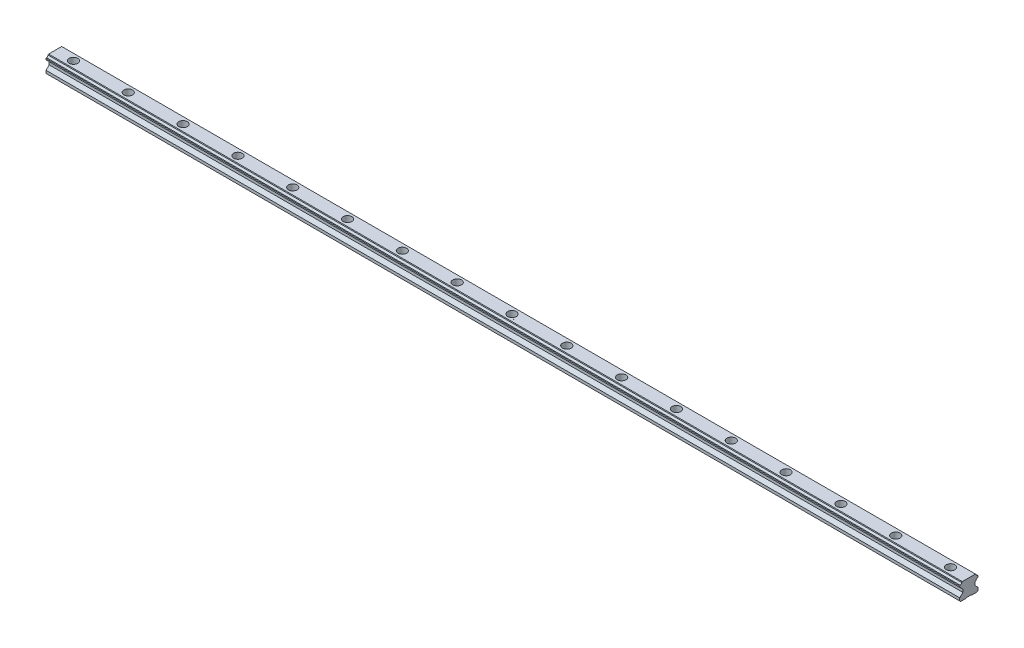
SolidWorks part; units mm, degrees
material "Alloy Steel"
ref_plane "Front Plane" through (0, 0, 0) normal (0, 0, 1) x (1, 0, 0)
ref_plane "Top Plane" through (0, 0, 0) normal (0, 1, 0) x (1, 0, 0)
ref_plane "Right Plane" through (0, 0, 0) normal (1, 0, 0) x (0, 0, -1)
sketch "Sketch6" plane through (0, 48.7499, 0) normal (0, 1, 0) x (-1, 0, 0)
  line L0 (-67, -46.0009) -> (-233, -46.0009) construction
  line L1 (-124.6001, -68.0009) -> (-124.6001, -24.0009)
  line L2 (-175.4001, -68.0009) -> (-175.4001, -24.0009)
  line L3 (-70, -56.0009) -> (-70, -36.0009)
  line L4 (-116.0002, -67.0009) -> (-116.0002, -25.0009)
  line L5 (-115.0002, -67.0009) -> (-115.0002, -25.0009)
  line L6 (-113.0002, -56.4008) -> (-113.0002, -35.601)
  line L7 (-115.0002, -67.0009) -> (-124.6001, -67.0009)
  line L8 (-113.0002, -56.4008) -> (-115.0002, -58.4008)
  line L9 (-70, -56.0009) -> (-113.0002, -56.0009)
  line L10 (-70, -53.1609) -> (-113.0002, -53.1609)
  line L11 (-113.0002, -35.601) -> (-115.0002, -33.601)
  line L12 (-115.0002, -25.0009) -> (-124.6001, -25.0009)
  line L13 (-70, -38.841) -> (-103.6509, -38.841)
  line L14 (-70, -36.0009) -> (-104.6381, -36.0009)
  line L15 (-230, -56.0009) -> (-230, -36.0009)
  line L16 (-230, -36.0009) -> (-187, -36.0009)
  line L17 (-184, -67.0009) -> (-184, -25.0009)
  line L18 (-185, -67.0009) -> (-185, -25.0009)
  line L19 (-187, -56.4008) -> (-187, -35.601)
  line L20 (-185, -67.0009) -> (-175.4001, -67.0009)
  line L21 (-187, -56.4008) -> (-185, -58.4008)
  line L22 (-230, -56.0009) -> (-187, -56.0009)
  line L23 (-230.0002, -53.1609) -> (-187, -53.1609)
  line L24 (-187, -35.601) -> (-185, -33.601)
  line L25 (-185, -25.0009) -> (-175.4001, -25.0009)
  line L26 (-230.0002, -38.841) -> (-187, -38.841)
  line L27 (-210, -52.0009) -> (-210, -40.0009) construction
  line L28 (-90, -52.0009) -> (-90, -40.0009) construction
  line L29 (-150, -52.0009) -> (-150, -40.0009) construction
  line L30 (-182.2712, -57.0009) -> (-187.2456, -57.0009) construction
  line L31 (-182.2712, -35.0009) -> (-187.2456, -35.0009) construction
  line L32 (-117.7288, -57.0009) -> (-112.7544, -57.0009) construction
  line L33 (-117.7288, -35.0009) -> (-112.7544, -35.0009) construction
  line L34 (-113.0003, -42.0009) -> (-113.0003, -50.0009)
  line L35 (-109.7003, -50.0009) -> (-113.0003, -50.0009)
  line L36 (-111.3204, -42.0009) -> (-113.0003, -42.0009)
  line L37 (-105.7003, -46.0009) -> (-105.7003, -44.3288)
  line L38 (-113.0003, -50.0009) -> (-115.0002, -50.0009)
  line L39 (-113.0003, -42.0009) -> (-115.0002, -42.0009)
  line L40 (-103.483, -36.4794) -> (-107.9177, -34.6425)
  line L41 (-103.6848, -39.3183) -> (-109.7824, -36.7926)
  line L42 (-103.483, -36.4794) -> (-103.6848, -39.3183)
  line L43 (-107.9177, -34.6425) -> (-109.7824, -36.7926)
  line L44 (-104.4235, -43.0391) -> (-104.8382, -44.0402)
  line L45 (-111.8911, -39.946) -> (-112.3058, -40.947)
  line L46 (-105.6176, -44.363) -> (-104.8382, -44.0402)
  line L47 (-106.0608, -41.7115) -> (-106.9334, -43.8181)
  line L48 (-109.7946, -40.1649) -> (-110.6671, -42.2715)
  line L49 (-105.6176, -44.363) -> (-111.9829, -41.7265)
  line L50 (-112.3058, -40.947) -> (-111.9829, -41.7265)
  line L51 (-104.6533, -42.2945) -> (-111.2021, -39.5819)
  line L52 (-110.2333, -38.841) -> (-113.0002, -38.841)
  line L53 (-109.0958, -36.0009) -> (-113.0002, -36.0009)
  line L54 (-124.6001, -53.0009) -> (-175.4001, -53.0009)
  line L55 (-124.6001, -68.0009) -> (-175.4001, -68.0009)
  line L56 (-124.6001, -39.0009) -> (-175.4001, -39.0009)
  line L57 (-124.6001, -24.0009) -> (-175.4001, -24.0009)
  line L58 (-135.5002, -30.0009) -> (-128.5002, -30.0009) construction
  line L59 (-132.0002, -33.5009) -> (-132.0002, -26.5009) construction
  line L60 (-135.5002, -62.0009) -> (-128.5002, -62.0009) construction
  line L61 (-132.0002, -58.5009) -> (-132.0002, -65.5009) construction
  line L62 (-164.4998, -62.0009) -> (-171.4998, -62.0009) construction
  line L63 (-167.9998, -58.5009) -> (-167.9998, -65.5009) construction
  line L64 (-167.9998, -33.5009) -> (-167.9998, -26.5009) construction
  line L65 (-164.4998, -30.0009) -> (-171.4998, -30.0009) construction
  line L66 (-105.0017, -33.8739) -> (-110.025, -46.0009) construction
  circle A0 centre (-210, -46.0009) radius 4.75
  circle A1 centre (-210, -46.0009) radius 3
  circle A2 centre (-90, -46.0009) radius 4.75
  circle A3 centre (-90, -46.0009) radius 3
  arc A4 (-104.5435, -40.5239) -> (-103.6848, -39.3183) centre (-106.7336, -38.0554) ccw
  arc A5 (-109.7824, -36.7926) -> (-110.0277, -38.2523) centre (-106.7336, -38.0555) ccw
  arc A6 (-104.8118, -41.1563) -> (-104.4235, -43.0391) centre (-98.8173, -40.9014) ccw
  arc A7 (-111.8911, -39.946) -> (-110.2851, -38.8892) centre (-114.3437, -34.4701) ccw
  arc A8 (-104.5435, -40.5239) -> (-104.8118, -41.1563) centre (-104.0126, -41.1223) ccw
  arc A9 (-110.2851, -38.8892) -> (-110.0277, -38.2523) centre (-110.8263, -38.3) ccw
  arc A10 (-109.7003, -50.0009) -> (-105.7003, -46.0009) centre (-109.7003, -46.0009) ccw
  circle A11 centre (-132.0002, -30.0009) radius 2.1499
  circle A12 centre (-132.0002, -30.0009) radius 2.5
sketch "Sketch7" plane through (0, 0, 0) normal (0, 0, 1) x (1, 0, 0)
  line L0 (70, 36.7499) -> (113.0002, 36.7499)
  line L1 (70, 22.7499) -> (230, 22.7499)
  line L2 (70, 18.7499) -> (230, 18.7499)
  line L3 (187, 36.7499) -> (230, 36.7499)
  line L4 (124.6001, 48.7499) -> (124.6001, 24.2499)
  line L5 (175.4001, 48.7499) -> (175.4001, 24.2499)
  line L6 (131.6984, 23.4559) -> (131.7153, 24.2498)
  line L7 (128.2851, 24.2498) -> (128.3021, 23.4559)
  line L8 (116.0002, 47.9498) -> (116.0002, 24.2496)
  line L9 (115.0002, 48.3698) -> (115.0002, 24.2496)
  line L10 (113.0002, 37.1498) -> (113.0002, 24.2496)
  line L11 (113.0002, 37.1498) -> (115.0002, 39.1496)
  line L12 (113.0002, 24.2496) -> (187, 24.2496)
  line L13 (101.8003, 43.7494) -> (117.729, 43.7494) construction
  line L14 (113.0005, 39.6295) -> (113.0005, 47.8695)
  line L15 (110.0005, 47.7494) -> (113.0005, 47.7494)
  line L16 (115.0002, 48.3698) -> (113.5002, 48.3695)
  line L17 (115.0002, 46.0594) -> (113.0005, 46.0594)
  line L18 (115.0002, 39.1295) -> (113.5002, 39.1295)
  line L19 (115.0002, 41.4396) -> (113.0005, 41.4396)
  line L20 (113.5002, 39.1295) -> (113.0005, 39.6295)
  line L21 (113.0005, 47.8695) -> (113.5002, 48.3695)
  line L22 (111.1003, 40.2494) -> (105.9004, 40.2494)
  line L23 (111.1003, 40.2096) -> (111.1003, 40.2494)
  line L24 (112.6004, 43.7496) -> (111.1003, 40.2494)
  line L25 (111.7006, 43.7494) -> (110.1005, 40.2494)
  line L26 (105.9004, 40.2494) -> (105.5003, 40.8294)
  line L27 (105.9, 47.2496) -> (105.5, 46.6696)
  line L28 (111.1003, 47.2494) -> (105.9, 47.2496)
  line L29 (111.7006, 43.7494) -> (110.1003, 47.2495)
  line L30 (112.6004, 43.7496) -> (111.1003, 47.2494)
  line L31 (110.0005, 39.7494) -> (113.0005, 39.7494)
  line L32 (111.1003, 40.2096) -> (111.1003, 40.2494)
  line L33 (114.6187, 41.5681) -> (115.0003, 41.5347)
  line L34 (114.6185, 45.931) -> (115.0003, 45.9644)
  line L35 (184, 24.2496) -> (184, 47.9498)
  line L36 (185, 24.2496) -> (185, 47.9498)
  line L37 (187, 24.2496) -> (187, 37.1498)
  line L38 (185.0002, 39.1495) -> (187, 37.1498)
  line L39 (175.4001, 47.9498) -> (185, 47.9498)
  line L40 (182.2712, 43.7494) -> (187.2456, 43.7494) construction
  line L41 (115.0002, 47.9498) -> (124.6001, 47.9498)
  line L42 (130.0003, 25.5223) -> (130.0003, 21.4961) construction
  line L43 (170, 25.5222) -> (170, 21.496) construction
  line L44 (210, 38.7499) -> (210, 16.521) construction
  line L45 (70, 36.7499) -> (70, 18.7499)
  line L46 (230, 36.7499) -> (230, 18.7499)
  line L47 (94.75, 36.7499) -> (94.75, 28.2499) construction
  line L48 (85.25, 28.2499) -> (94.75, 28.2499) construction
  line L49 (93, 28.2499) -> (93, 18.7499) construction
  line L50 (87, 28.2499) -> (87, 18.7499) construction
  line L51 (85.25, 36.7499) -> (85.25, 28.2499) construction
  line L52 (90, 38.7499) -> (90, 16.521) construction
  line L53 (150, 38.7499) -> (150, 16.521) construction
  line L54 (70, 33.9098) -> (113.0002, 33.9098)
  line L55 (70, 32.5797) -> (113.0002, 32.5797)
  line L56 (187, 33.9098) -> (230, 33.9098)
  line L57 (187, 32.5797) -> (230, 32.5797)
  line L58 (124.6001, 48.7499) -> (175.4001, 48.7499)
  line L59 (124.6001, 40.7497) -> (175.4001, 40.7497)
  line L60 (132.0002, 39.8278) -> (132.0002, 50.2497) construction
  line L61 (168, 39.8278) -> (168, 50.2497) construction
  line L62 (70, 30.3455) -> (113.0002, 30.3455)
  line L63 (187, 30.3455) -> (230, 30.3455)
  arc A0 (128.7304, 22.9325) -> (131.2696, 22.9325) centre (130, 27.2497) ccw
  arc A1 (128.3021, 23.4559) -> (128.7304, 22.9325) centre (128.8998, 23.5081) ccw
  arc A2 (131.2696, 22.9325) -> (131.6984, 23.4559) centre (131.1007, 23.5082) ccw
  arc A3 (110.0005, 47.7494) -> (108.0921, 47.2653) centre (109.9996, 43.7494) ccw
  arc A4 (108.1005, 40.2499) -> (110.0005, 39.7674) centre (110.0005, 43.7499) ccw
  arc A5 (113.9171, 45.3473) -> (113.9171, 42.152) centre (119.7004, 43.7496) ccw
  arc A6 (114.6185, 45.931) -> (113.9171, 45.3473) centre (114.6881, 45.134) ccw
  arc A7 (113.9171, 42.152) -> (114.6187, 41.5681) centre (114.6882, 42.3651) ccw
  arc A8 (105.7008, 46.2499) -> (104.7887, 46.0449) centre (105.7035, 44.1063) ccw
  arc A9 (104.7887, 46.0449) -> (104.0413, 45.4809) centre (105.7763, 43.9588) ccw
  arc A10 (104.0413, 45.4809) -> (103.5635, 44.6741) centre (105.9462, 43.8081) ccw
  arc A11 (103.5635, 44.6741) -> (103.4004, 43.7502) centre (106.0925, 43.7513) ccw
  arc A12 (103.4004, 43.7502) -> (103.5629, 42.8265) centre (106.092, 43.7475) ccw
  arc A13 (103.5629, 42.8265) -> (104.04, 42.0196) centre (105.9452, 43.6906) ccw
  arc A14 (104.04, 42.0196) -> (104.7881, 41.4548) centre (105.7751, 43.5399) ccw
  arc A15 (104.7881, 41.4548) -> (105.7007, 41.2499) centre (105.7025, 43.3929) ccw
  arc A16 (105.7007, 41.2499) -> (106.6128, 41.4552) centre (105.6973, 43.3935) ccw
  arc A17 (106.6128, 41.4552) -> (107.36, 42.0194) centre (105.6245, 43.5411) ccw
  arc A18 (107.36, 42.0194) -> (107.8376, 42.8263) centre (105.4545, 43.6918) ccw
  arc A19 (107.8376, 42.8263) -> (108.0004, 43.7502) centre (105.3084, 43.7485) ccw
  arc A20 (108.0004, 43.7502) -> (107.8378, 44.6738) centre (105.3089, 43.7523) ccw
  arc A21 (107.8378, 44.6738) -> (107.3605, 45.4806) centre (105.4558, 43.8092) ccw
  arc A22 (107.3605, 45.4806) -> (106.6122, 46.0453) centre (105.6259, 43.96) ccw
  arc A23 (106.6122, 46.0453) -> (105.6997, 46.2499) centre (105.6983, 44.1069) ccw
  arc A24 (104.5765, 41.5688) -> (105.2727, 40.9529) centre (106.9306, 43.5287) ccw
  arc A25 (105.2727, 40.9529) -> (106.1252, 40.5833) centre (106.8262, 43.3679) ccw
  arc A26 (106.1252, 40.5833) -> (107.0502, 40.5112) centre (106.8005, 43.2757) ccw
  arc A27 (107.0502, 40.5112) -> (107.9468, 40.7465) centre (106.7945, 43.3114) ccw
  arc A28 (107.9468, 40.7465) -> (108.7234, 41.2552) centre (106.7298, 43.4512) ccw
  arc A29 (108.7234, 41.2552) -> (109.3127, 41.9734) centre (106.5851, 43.6108) ccw
  arc A30 (109.3127, 41.9734) -> (109.6775, 42.8287) centre (106.4133, 43.7155) ccw
  arc A31 (109.6775, 42.8287) -> (109.8005, 43.7499) centre (106.2983, 43.7488) ccw
  arc A32 (109.8005, 43.7499) -> (109.6773, 44.6717) centre (106.2983, 43.7509) ccw
  arc A33 (109.6773, 44.6717) -> (109.3127, 45.5264) centre (106.4134, 43.7843) ccw
  arc A34 (109.3127, 45.5264) -> (108.7231, 46.2448) centre (106.5851, 43.889) ccw
  arc A35 (108.7231, 46.2448) -> (107.9455, 46.7539) centre (106.7299, 44.0488) ccw
  arc A36 (107.9455, 46.7539) -> (107.047, 46.9889) centre (106.7945, 44.1886) ccw
  arc A37 (107.047, 46.9889) -> (106.1224, 46.9158) centre (106.8005, 44.2239) ccw
  arc A38 (106.1224, 46.9158) -> (105.2712, 46.5459) centre (106.8263, 44.1315) ccw
  arc A39 (105.2712, 46.5459) -> (104.5758, 45.9302) centre (106.9308, 43.9708) ccw
sketch "Sketch8" plane through (46.0009, 0, 0) normal (-1, 0, 0) x (0, 0, 1)
  line L0 (-37.0009, 19.5499) -> (-43.0009, 19.5499)
  line L1 (-39.4509, 29.9298) -> (-39.4509, 26.9999)
  line L2 (-52.5507, 29.9298) -> (-52.5507, 26.9999)
  line L3 (-39.4509, 26.9999) -> (-37.7009, 25.2499)
  line L4 (-59.4009, 25.2498) -> (-54.3007, 25.2499)
  line L5 (-56.0005, 20.5496) -> (-55.0004, 19.5496)
  line L6 (-36.0005, 20.5495) -> (-37.0009, 19.5499)
  line L7 (-56.0006, 23.5496) -> (-56.0005, 20.5496)
  line L8 (-36.0006, 23.5497) -> (-36.0005, 20.5495)
  line L9 (-48.5009, 20.0499) -> (-43.5009, 20.0499)
  line L10 (-49.0007, 19.5499) -> (-48.5009, 20.0499)
  line L11 (-43.5009, 20.0499) -> (-43.0009, 19.5499)
  line L12 (-49.0007, 19.5499) -> (-55.0004, 19.5496)
  line L13 (-62.0009, 25.2499) -> (-62.0009, 25.0499)
  line L14 (-30.0009, 25.0499) -> (-30.0009, 25.2499)
  line L15 (-25.0005, 27.2496) -> (-27.0005, 25.2496)
  line L16 (-37.7009, 25.2499) -> (-34.3325, 25.2499)
  line L17 (-37.2009, 28.9813) -> (-37.2009, 28.1183)
  line L18 (-37.2009, 28.1183) -> (-34.3325, 25.2499)
  line L19 (-57.7024, 24.256) -> (-57.6679, 25.2496)
  line L20 (-61.1328, 25.2497) -> (-61.0984, 24.2561)
  line L21 (-65.0005, 25.2497) -> (-67.0005, 27.2496)
  line L22 (-65.0005, 25.2497) -> (-62.0009, 25.2497)
  line L23 (-54.8007, 28.1183) -> (-54.8007, 28.9813)
  line L24 (-57.669, 25.2497) -> (-54.8007, 28.1183)
  line L25 (-59.4009, 26.7499) -> (-59.4009, 22.65) construction
  line L26 (-32.601, 26.7499) -> (-32.601, 22.65) construction
  line L27 (-50.7509, 29.0499) -> (-41.2509, 29.0499) construction
  line L28 (-43.0009, 29.0499) -> (-43.0009, 19.5499) construction
  line L29 (-49.0009, 29.0499) -> (-49.0007, 19.5499) construction
  line L30 (-46.0009, 51.5499) -> (-46.0009, 17.5499) construction
  line L31 (-36.0009, 34.7098) -> (-36.0009, 33.3798)
  line L32 (-38.8405, 37.5495) -> (-38.2327, 36.9417)
  line L33 (-56.0009, 34.7098) -> (-56.0009, 33.3798)
  line L34 (-39.4509, 29.9298) -> (-38.2345, 31.1456)
  line L35 (-53.1609, 37.5499) -> (-38.8405, 37.5495)
  line L36 (-56.0009, 33.3798) -> (-55.485, 32.8641)
  line L37 (-56.0009, 34.7098) -> (-55.473, 35.2369)
  line L38 (-53.7666, 31.1457) -> (-52.5507, 29.9298)
  line L39 (-45.2756, 48.7499) -> (-27.0008, 48.7499)
  line L40 (-53.7684, 36.9415) -> (-53.1609, 37.5499)
  line L41 (-36.5281, 35.2371) -> (-36.0009, 34.7098)
  line L42 (-36.5161, 32.864) -> (-36.0009, 33.3798)
  line L43 (-51.0009, 44.5499) -> (-32.0041, 44.5499) construction
  line L44 (-46.0013, 49.1689) -> (-44.0631, 48.0499)
  line L45 (-50.7509, 37.5499) -> (-50.7509, 29.0499) construction
  line L46 (-41.2509, 37.5499) -> (-41.2509, 29.0499) construction
  line L47 (-35.0009, 47.5497) -> (-35.0009, 41.5497) construction
  line L48 (-60.0009, 44.5497) -> (-54.0009, 44.5497) construction
  line L49 (-54.1543, 39.9498) -> (-37.8474, 39.9498)
  line L50 (-37.8474, 39.9498) -> (-33.6005, 35.7029)
  line L51 (-65.0011, 48.7499) -> (-46.726, 48.7499)
  line L52 (-50.0009, 46.8597) -> (-50.0009, 42.2404)
  line L53 (-50.0009, 46.8597) -> (-46.0013, 49.1689)
  line L54 (-25.0009, 46.7499) -> (-25.0005, 27.2496)
  line L55 (-27.0008, 48.7499) -> (-25.0009, 46.7499)
  line L56 (-50.0009, 42.2404) -> (-46.0004, 39.9307)
  line L57 (-33.6005, 35.7029) -> (-33.6008, 32.5814)
  line L58 (-37.2009, 28.9813) -> (-33.6008, 32.5814)
  line L59 (-67.0005, 27.2496) -> (-67.0009, 46.75)
  line L60 (-58.4008, 32.5814) -> (-58.4008, 35.7033)
  line L61 (-58.4008, 32.5814) -> (-54.8007, 28.9813)
  line L62 (-65.0011, 48.7499) -> (-67.0009, 46.75)
  line L63 (-57.0009, 41.5497) -> (-57.0009, 47.5497) construction
  line L64 (-58.4008, 35.7033) -> (-54.1543, 39.9498)
  line L65 (-46.0004, 39.9307) -> (-44.0528, 41.05)
  line L66 (-38.2342, 41.3038) -> (-35.4801, 42.0495)
  line L67 (-40.0506, 41.5197) -> (-40.1406, 41.0497)
  line L68 (-42.5604, 44.5498) -> (-41.9104, 41.0498)
  line L69 (-44.8706, 44.5494) -> (-44.2206, 41.0492)
  line L70 (-44.2206, 41.0492) -> (-40.1406, 41.0497)
  line L71 (-38.2508, 47.7997) -> (-35.4807, 47.0497)
  line L72 (-40.0504, 47.5696) -> (-40.1404, 48.0495)
  line L73 (-42.5604, 44.5498) -> (-41.9104, 48.0496)
  line L74 (-44.8706, 44.5494) -> (-44.2208, 48.0497)
  line L75 (-44.2208, 48.0497) -> (-40.1404, 48.0495)
  line L76 (-68.0009, 48.5497) -> (-68.0009, 41.5499)
  line L77 (-67.7009, 41.2501) -> (-67.7009, 26.0526)
  line L78 (-67.6988, 41.2507) -> (-67.9988, 41.5508)
  line L79 (-66.9983, 49.5493) -> (-67.9984, 48.5492)
  line L80 (-67.0009, 49.5499) -> (-53.5007, 49.5499)
  line L81 (-64.1508, 49.5499) -> (-64.1508, 42.5499) construction
  line L82 (-64.5009, 49.5499) -> (-64.5009, 43.5499) construction
  line L83 (-64.5009, 43.5499) -> (-59.5009, 43.5499) construction
  line L84 (-64.1508, 42.5499) -> (-59.8508, 42.5499) construction
  line L85 (-64.1497, 42.55) -> (-61.9996, 41.3087) construction
  line L86 (-59.8488, 42.5498) -> (-61.9996, 41.3087) construction
  line L87 (-62.0009, 51.0499) -> (-62.0009, 40.6281) construction
  line L88 (-59.5009, 49.5499) -> (-59.5009, 43.5499) construction
  line L89 (-59.8508, 49.5499) -> (-59.8508, 42.5499) construction
  line L90 (-59.5009, 43.5499) -> (-59.8501, 42.9434) construction
  line L91 (-64.4989, 43.5499) -> (-64.1489, 42.9437) construction
  line L92 (-67.6988, 26.0505) -> (-66.6987, 25.0504)
  line L93 (-66.7009, 25.0499) -> (-62.0009, 25.0499)
  line L94 (-30.0009, 25.0499) -> (-25.3007, 25.0499)
  line L95 (-24.2991, 26.0506) -> (-25.2991, 25.0505)
  line L96 (-24.3007, 41.2501) -> (-24.3007, 26.0499)
  line L97 (-24.0009, 48.5497) -> (-24.0009, 41.5499)
  line L98 (-24.2991, 41.2507) -> (-23.9991, 41.5507)
  line L99 (-24.9997, 49.5495) -> (-23.9996, 48.5494)
  line L100 (-38.5009, 49.5499) -> (-25.0009, 49.5499)
  line L101 (-53.0009, 49.0499) -> (-46.2075, 49.0499)
  line L102 (-52.9991, 49.0506) -> (-53.499, 49.5505)
  line L103 (-45.7951, 49.0499) -> (-39.0009, 49.0499)
  line L104 (-38.9989, 49.0505) -> (-38.4989, 49.5504)
  line L105 (-30.0009, 51.0499) -> (-30.0009, 40.6281) construction
  line L106 (-45.2756, 48.7499) -> (-46.726, 48.7499)
  line L107 (-45.7951, 49.0499) -> (-46.2075, 49.0499)
  line L108 (-54.3007, 25.2499) -> (-52.5507, 26.9999)
  line L109 (-37.7009, 25.2499) -> (-39.4509, 26.9999)
  line L110 (-30.0009, 25.2499) -> (-27.0005, 25.2496)
  line L111 (-30.0009, 25.2497) -> (-27.0005, 25.2496)
  line L112 (-30.0009, 25.2497) -> (-34.3325, 25.2499)
  line L113 (-62.0009, 25.2497) -> (-61.1328, 25.2497)
  line L114 (-59.4009, 25.2498) -> (-61.1328, 25.2497)
  line L115 (-56.0006, 23.5496) -> (-54.3007, 25.2499)
  line L116 (-37.7009, 25.2499) -> (-36.0006, 23.5497)
  arc A0 (-60.6705, 23.7327) -> (-58.1313, 23.7327) centre (-59.4009, 28.0499) ccw
  arc A1 (-61.0984, 24.2561) -> (-60.6705, 23.7327) centre (-60.5007, 24.3082) ccw
  arc A2 (-58.1313, 23.7327) -> (-57.7024, 24.256) centre (-58.3001, 24.3085) ccw
  arc A3 (-55.473, 35.2369) -> (-53.7684, 36.9415) centre (-55.8019, 37.2705) ccw
  arc A4 (-36.5161, 32.864) -> (-38.2345, 31.1456) centre (-36.199, 30.8285) ccw
  arc A5 (-53.7666, 31.1457) -> (-55.485, 32.8641) centre (-55.8021, 30.8286) ccw
  arc A6 (-38.2327, 36.9417) -> (-36.5281, 35.2371) centre (-36.1991, 37.2707) ccw
  arc A7 (-44.0684, 48.0497) -> (-44.0684, 41.0497) centre (-46.0009, 44.5497) ccw
  arc A8 (-38.2508, 47.7997) -> (-39.1823, 47.4008) centre (-38.3908, 46.8397) ccw
  arc A9 (-48.0009, 41.0856) -> (-47.9374, 41.0497) centre (-46.0009, 44.5497) ccw
  arc A10 (-39.1808, 41.6999) -> (-40.3645, 41.2349) centre (-39.3808, 40.4699) ccw
  arc A11 (-39.1808, 41.6999) -> (-38.2511, 41.3017) centre (-38.3909, 42.2599) ccw
  arc A12 (-53.7422, 30.8287) -> (-53.7423, 30.8413) centre (-55.8022, 30.8287) ccw
  arc A13 (-35.0661, 42.3006) -> (-35.0661, 46.7987) centre (-35.0009, 44.5497) ccw
  circle A14 centre (-57.0009, 44.5497) radius 2.25
  arc A15 (-40.3708, 47.8598) -> (-39.1795, 47.3918) centre (-39.3808, 48.6298) ccw
  arc A16 (-38.2508, 47.7997) -> (-38.6658, 47.6155) centre (-38.2229, 47.1773) ccw
  arc A17 (-38.6658, 47.6155) -> (-38.9472, 47.2488) centre (-37.6054, 46.5103) ccw
  arc A18 (-38.9472, 47.2488) -> (-39.1426, 46.8273) centre (-36.3787, 45.8019) ccw
  arc A19 (-39.1426, 46.8273) -> (-39.2828, 46.384) centre (-34.9363, 45.2534) ccw
  arc A20 (-39.2828, 46.384) -> (-39.3827, 45.9292) centre (-33.5437, 44.8846) ccw
  arc A21 (-39.3827, 45.9292) -> (-39.45, 45.4683) centre (-32.3728, 44.6714) ccw
  arc A22 (-39.45, 45.4683) -> (-39.4887, 45.004) centre (-31.5386, 44.5752) ccw
  arc A23 (-39.4887, 45.004) -> (-39.5009, 44.5383) centre (-31.1105, 44.5503) ccw
  arc A24 (-39.5009, 44.5383) -> (-39.4875, 44.074) centre (-31.121, 44.5488) ccw
  arc A25 (-39.4875, 44.074) -> (-39.4476, 43.6103) centre (-31.568, 44.5218) ccw
  arc A26 (-39.4476, 43.6103) -> (-39.3788, 43.1484) centre (-32.4201, 44.421) ccw
  arc A27 (-39.3788, 43.1484) -> (-39.2771, 42.6938) centre (-33.6062, 44.201) ccw
  arc A28 (-39.2771, 42.6938) -> (-39.1344, 42.2504) centre (-35.0079, 43.8233) ccw
  arc A29 (-39.1344, 42.2504) -> (-38.9349, 41.8294) centre (-36.4501, 43.2643) ccw
  arc A30 (-38.9349, 41.8294) -> (-38.6456, 41.4659) centre (-37.6601, 42.5472) ccw
  arc A31 (-38.6456, 41.4659) -> (-38.2231, 41.3005) centre (-38.2334, 41.8964) ccw
  arc A32 (-35.4807, 47.0497) -> (-36.0107, 46.6248) centre (-35.3565, 46.3517) ccw
  arc A33 (-36.0107, 46.6248) -> (-36.2648, 45.9619) centre (-33.5257, 45.2921) ccw
  arc A34 (-36.2648, 45.9619) -> (-36.3916, 45.2619) centre (-31.3605, 44.7126) ccw
  arc A35 (-36.3916, 45.2619) -> (-36.4309, 44.5497) centre (-30.0542, 44.5544) ccw
  arc A36 (-36.4309, 44.5497) -> (-36.3918, 43.8395) centre (-30.0528, 44.545) ccw
  arc A37 (-36.3918, 43.8395) -> (-36.2653, 43.1393) centre (-31.3554, 44.3877) ccw
  arc A38 (-36.2653, 43.1393) -> (-36.0113, 42.4755) centre (-33.5214, 43.8089) ccw
  arc A39 (-36.0113, 42.4755) -> (-35.4809, 42.0497) centre (-35.3563, 42.7481) ccw
  arc A40 (-35.4809, 42.0497) -> (-34.9511, 42.4746) centre (-35.6052, 42.7474) ccw
  arc A41 (-34.9511, 42.4746) -> (-34.697, 43.1375) centre (-37.4361, 43.8073) ccw
  arc A42 (-34.697, 43.1375) -> (-34.5703, 43.8375) centre (-39.6014, 44.3868) ccw
  arc A43 (-34.5703, 43.8375) -> (-34.5309, 44.5497) centre (-40.9077, 44.545) ccw
  arc A44 (-34.5309, 44.5497) -> (-34.5701, 45.2598) centre (-40.909, 44.5544) ccw
  arc A45 (-34.5701, 45.2598) -> (-34.6966, 45.9601) centre (-39.6064, 44.7117) ccw
  arc A46 (-34.6966, 45.9601) -> (-34.9506, 46.6239) centre (-37.4405, 45.2904) ccw
  arc A47 (-34.9506, 46.6239) -> (-35.4807, 47.0497) centre (-35.6055, 46.3515) ccw
ref_plane "Plane2" through (46.0009, 0, 0) normal (-1, 0, 0) x (0, 0, 1)
ref_plane "Plane8" through (46.0009, 0, 0) normal (-1, 0, 0) x (0, 0, 1)
ref_plane "Plane9" through (70.0009, 0, 0) normal (-1, 0, 0) x (0, 0, 1)
ref_plane "Plane7" through (70.0009, 0, 0) normal (-1, 0, 0) x (0, 0, 1)
sketch "Sketch23" plane through (70.0009, 0, 0) normal (-1, 0, 0) x (0, 0, 1)
  line L0 (-49.0007, 19.5499) -> (-55.0004, 19.5496) construction
  line L1 (-56.0005, 20.5496) -> (-55.0004, 19.5496) construction
  line L2 (-56.0006, 23.5496) -> (-56.0005, 20.5496) construction
  line L3 (-48.5009, 20.0499) -> (-43.5009, 20.0499) construction
  line L4 (-49.0007, 19.5499) -> (-48.5009, 20.0499) construction
  line L5 (-56.0006, 23.5496) -> (-54.3007, 25.2499) construction
  line L6 (-54.3007, 25.2499) -> (-52.5507, 26.9999) construction
  line L7 (-52.5507, 29.9298) -> (-52.5507, 26.9999) construction
  line L8 (-53.7666, 31.1457) -> (-52.5507, 29.9298) construction
  line L9 (-56.0009, 33.3798) -> (-55.485, 32.8641) construction
  line L10 (-56.0009, 34.7098) -> (-56.0009, 33.3798) construction
  line L11 (-56.0009, 34.7098) -> (-55.473, 35.2369) construction
  line L12 (-53.7684, 36.9415) -> (-53.1609, 37.5499) construction
  line L13 (-53.1609, 37.5499) -> (-38.8405, 37.5495) construction
  line L14 (-38.8405, 37.5495) -> (-38.2327, 36.9417) construction
  line L15 (-36.5281, 35.2371) -> (-36.0009, 34.7098) construction
  line L16 (-36.0009, 34.7098) -> (-36.0009, 33.3798) construction
  line L17 (-36.5161, 32.864) -> (-36.0009, 33.3798) construction
  line L18 (-39.4509, 29.9298) -> (-38.2345, 31.1456) construction
  line L19 (-39.4509, 29.9298) -> (-39.4509, 26.9999) construction
  line L20 (-39.4509, 26.9999) -> (-37.7009, 25.2499) construction
  line L21 (-37.7009, 25.2499) -> (-36.0006, 23.5497) construction
  line L22 (-36.0006, 23.5497) -> (-36.0005, 20.5495) construction
  line L23 (-36.0005, 20.5495) -> (-37.0009, 19.5499) construction
  line L24 (-37.0009, 19.5499) -> (-43.0009, 19.5499) construction
  line L25 (-43.5009, 20.0499) -> (-43.0009, 19.5499) construction
  line L26 (-49.0007, 19.5499) -> (-55.0004, 19.5496)
  line L27 (-56.0005, 20.5496) -> (-55.0004, 19.5496)
  line L28 (-56.0006, 23.5496) -> (-56.0005, 20.5496)
  line L29 (-48.5009, 20.0499) -> (-43.5009, 20.0499)
  line L30 (-49.0007, 19.5499) -> (-48.5009, 20.0499)
  line L31 (-56.0006, 23.5496) -> (-54.3007, 25.2499)
  line L32 (-54.3007, 25.2499) -> (-52.5507, 26.9999)
  line L33 (-52.5507, 29.9298) -> (-52.5507, 26.9999)
  line L34 (-53.7666, 31.1457) -> (-52.5507, 29.9298)
  line L35 (-56.0009, 33.3798) -> (-55.485, 32.8641)
  line L36 (-56.0009, 34.7098) -> (-56.0009, 33.3798)
  line L37 (-56.0009, 34.7098) -> (-55.473, 35.2369)
  line L38 (-53.7684, 36.9415) -> (-53.1609, 37.5499)
  line L39 (-53.1609, 37.5499) -> (-38.8405, 37.5495)
  line L40 (-38.8405, 37.5495) -> (-38.2327, 36.9417)
  line L41 (-36.5281, 35.2371) -> (-36.0009, 34.7098)
  line L42 (-36.0009, 34.7098) -> (-36.0009, 33.3798)
  line L43 (-36.5161, 32.864) -> (-36.0009, 33.3798)
  line L44 (-39.4509, 29.9298) -> (-38.2345, 31.1456)
  line L45 (-39.4509, 29.9298) -> (-39.4509, 26.9999)
  line L46 (-39.4509, 26.9999) -> (-37.7009, 25.2499)
  line L47 (-37.7009, 25.2499) -> (-36.0006, 23.5497)
  line L48 (-36.0006, 23.5497) -> (-36.0005, 20.5495)
  line L49 (-36.0005, 20.5495) -> (-37.0009, 19.5499)
  line L50 (-37.0009, 19.5499) -> (-43.0009, 19.5499)
  line L51 (-43.5009, 20.0499) -> (-43.0009, 19.5499)
  arc A0 (-53.7666, 31.1457) -> (-55.485, 32.8641) centre (-55.8021, 30.8286) ccw construction
  arc A1 (-55.473, 35.2369) -> (-53.7684, 36.9415) centre (-55.8019, 37.2705) ccw construction
  arc A2 (-38.2327, 36.9417) -> (-36.5281, 35.2371) centre (-36.1991, 37.2707) ccw construction
  arc A3 (-36.5161, 32.864) -> (-38.2345, 31.1456) centre (-36.199, 30.8285) ccw construction
  arc A4 (-53.7666, 31.1457) -> (-55.485, 32.8641) centre (-55.8021, 30.8286) ccw
  arc A5 (-55.473, 35.2369) -> (-53.7684, 36.9415) centre (-55.8019, 37.2705) ccw
  arc A6 (-38.2327, 36.9417) -> (-36.5281, 35.2371) centre (-36.1991, 37.2707) ccw
  arc A7 (-36.5161, 32.864) -> (-38.2345, 31.1456) centre (-36.199, 30.8285) ccw
extrude "Boss-Extrude16" add sketch "Sketch23" against normal blind 1000 separate body
sketch "Sketch24" plane through (0, 37.5485, 0.001) normal (0, 1, 0) x (1, 0, 0)
  line L0 (67, 46.0023) -> (233, 46.0023) construction
  line L1 (67, 46.0023) -> (233, 46.0023) construction
  line L2 (90, 52.0023) -> (90, 40.0023) construction
  line L3 (90, 52.0023) -> (90, 40.0023) construction
hole_wizard "CBORE for M3 SHCS1" positions "Sketch26" profile "Sketch27" counterbore size "M3" standard "Ansi Metric" end condition through all
sketch "Sketch26" plane through (0, 37.5485, 0.001) normal (0, 1, 0) x (-1, 0, 0)
  line L0 (-67, -46.0023) -> (-233, -46.0023) construction
  line L1 (-90, -52.0023) -> (-90, -40.0023) construction
  point P0 (-90, -46.0023)
sketch "Sketch27" plane through (90, 37.5497, -46.0012) normal (1, 0, 0) x (0, 0, 1)
  line L0 (0, 0) -> (0, 18.0004)
  line L1 (0, 18.0004) -> (3, 18.0004)
  line L3 (3, 18.0004) -> (3, 8.5)
  line L4 (3, 8.5) -> (4.75, 8.5)
  line L5 (4.75, 8.5) -> (4.75, 0)
  line L7 (4.75, 0) -> (0, 0)
  line L11 (0, -6.35) -> (0, 107.95) construction
  dimension "Thru Hole Dia." = 6
  dimension "Thru Hole Depth" = 18.0004
  dimension "C'Bore Dia." = 9.5
  dimension "C'Bore Depth" = 8.5
pattern_linear "LPattern1" count 17 spacing 60 along (1, 0, 0) of "CBORE for M3 SHCS1"
sketch "Sketch28" plane through (0, 37.5485, 0.001) normal (0, 1, 0) x (1, 0, 0)
  text T0 "HSR20 Rail"
